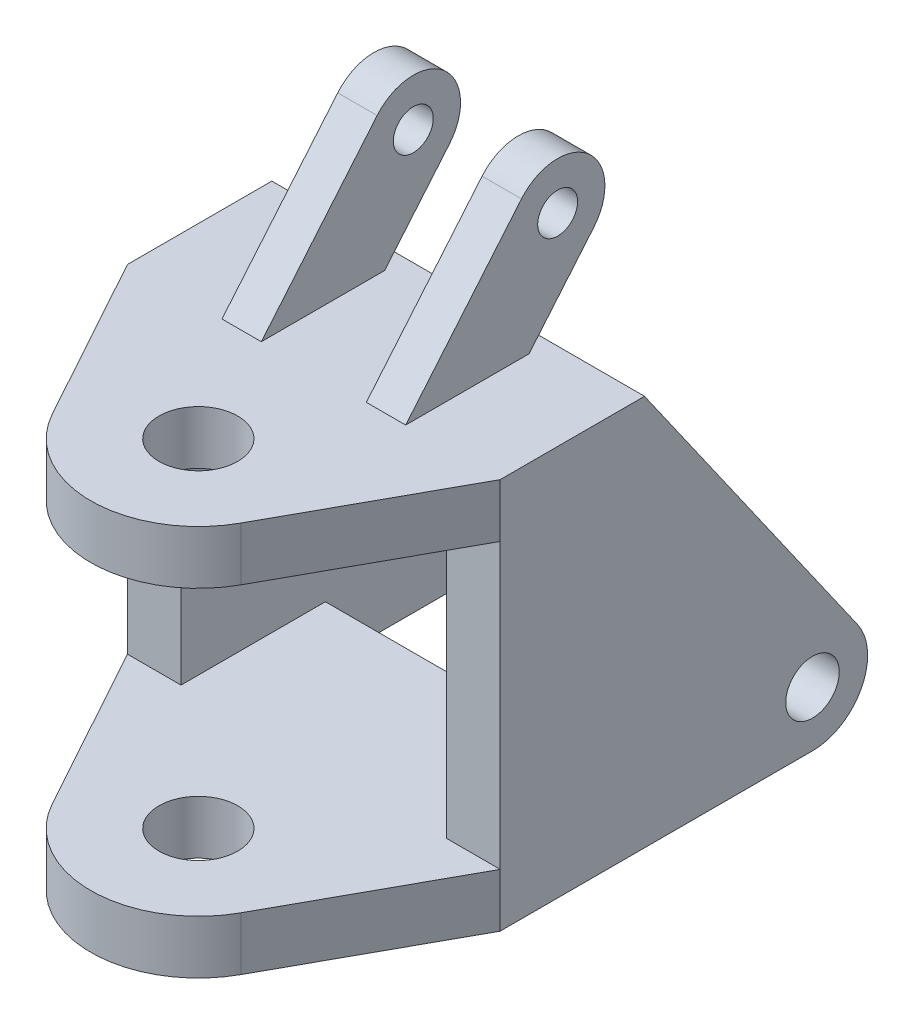
SolidWorks part; units mm, degrees
ref_plane "Front Plane" through (0, 0, 0) normal (0, 0, 1) x (1, 0, 0)
ref_plane "Top Plane" through (0, 0, 0) normal (0, 1, 0) x (1, 0, 0)
ref_plane "Right Plane" through (0, 0, 0) normal (1, 0, 0) x (0, 0, -1)
sketch "Sketch1" plane through (0, 0, 0) normal (0, 1, 0) x (1, 0, 0)
  line L0 (-179.6149, -98.8104) -> (-355, 220)
  line L1 (-355, 220) -> (-355, 495)
  line L2 (-355, 495) -> (355, 495)
  line L3 (355, 495) -> (355, 220)
  line L4 (355, 220) -> (179.6149, -98.8104)
  line L5 (0, 0) -> (0, 862.8745) construction
  line L6 (-355, 220) -> (355, 220) construction
  circle A0 centre (0, 0) radius 75
  arc A1 (-179.6149, -98.8104) -> (179.6149, -98.8104) centre (0, 0) ccw
  dimension "D1" = 150
  dimension "D2" = 205
  dimension "D3" = 710
  dimension "D4" = 495
  dimension "D5" = 220
extrude "Boss-Extrude1" add sketch "Sketch1" along normal blind 102
sketch "Sketch3" plane through (355, 0, 0) normal (1, 0, 0) x (0, 0, -1)
  line L0 (220, 0) -> (220, 745)
  line L1 (220, 745) -> (495, 745)
  line L2 (495, 745) -> (901.0076, 165.2304)
  line L4 (815, 0) -> (220, 0)
  circle A0 centre (815, 105) radius 51
  arc A1 (815, 0) -> (901.0076, 165.2304) centre (815, 105) ccw
  point P8 (649.3817, 58.7718)
  point P9 (0, 0)
  point P10 (699.2778, 55.9707)
  point P11 (0, 0)
  dimension "D1" = 102
  dimension "D2" = 105
  dimension "D3" = 745
  dimension "D4" = 595
  dimension "D5" = 495
extrude "Boss-Extrude2" add sketch "Sketch3" against normal blind 102
mirror "Mirror1" about plane through (0, 0, 0) normal (1, 0, 0) of "Boss-Extrude2"
ref_plane "Plane1" through (0, 372.5, 0) normal (0, -1, 0) x (-1, 0, 0)
mirror "Mirror2" about plane through (0, 372.5, 0) normal (0, -1, 0) of "Boss-Extrude1"
ref_plane "Plane2" through (100, 0, 0) normal (1, 0, 0) x (0, 0, -1)
sketch "Sketch4" plane through (100, 0, 0) normal (1, 0, 0) x (0, 0, -1)
  line L0 (440.5581, 1007.8509) -> (220, 745)
  line L1 (220, 745) -> (454.9733, 745)
  line L2 (454.9733, 745) -> (578.4461, 892.1491)
  line L3 (-98.8104, 745) -> (220, 745) construction
  circle A0 centre (509.5021, 950) radius 38
  arc A1 (578.4461, 892.1491) -> (440.5581, 1007.8509) centre (509.5021, 950) ccw
  dimension "D2" = 90
  dimension "D3" = 76
  dimension "D1" = 50
  dimension "D4" = 205
extrude "Boss-Extrude3" add sketch "Sketch4" along normal blind 75
mirror "Mirror3" about plane through (0, 0, 0) normal (1, 0, 0) of "Boss-Extrude3"
equation "\"D5@Sketch1\"=1125-105-595-205"
